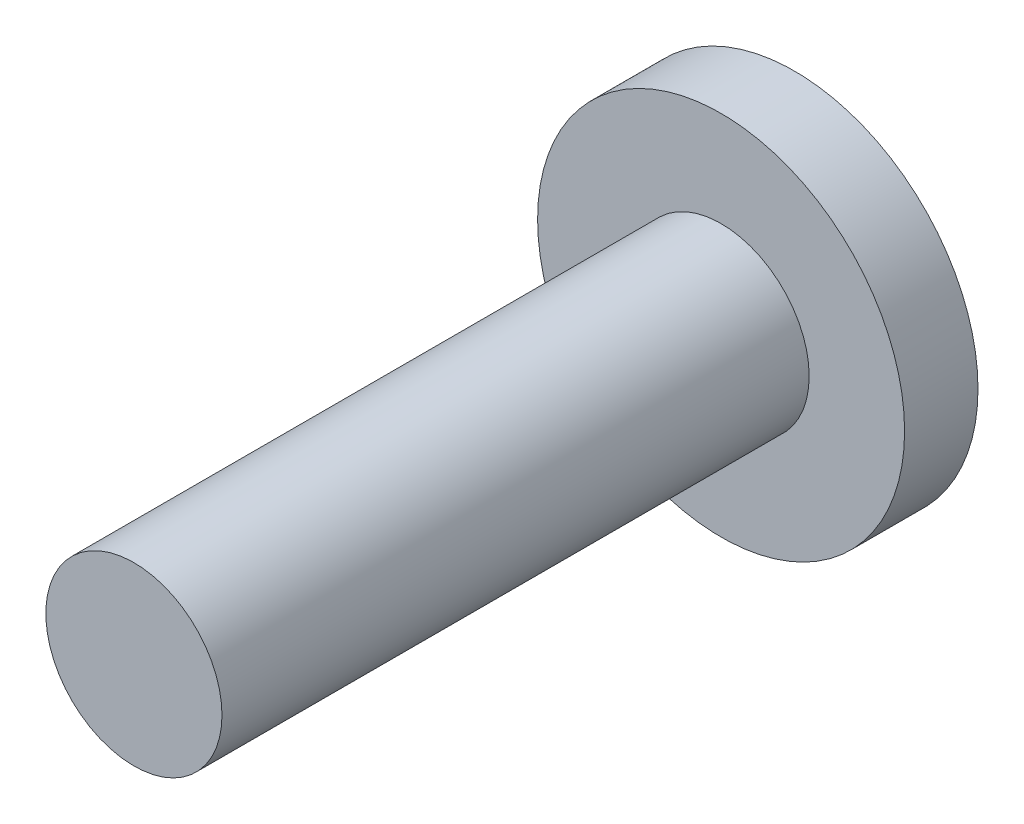
SolidWorks part; units mm, degrees
material "AISI 304"
ref_plane "前视基准面" through (0, 0, 0) normal (0, 0, 1) x (1, 0, 0)
ref_plane "上视基准面" through (0, 0, 0) normal (0, 1, 0) x (1, 0, 0)
ref_plane "右视基准面" through (0, 0, 0) normal (1, 0, 0) x (0, 0, -1)
other "Configuration Table"
sketch "草图1" plane through (0, 0, 0) normal (0, 0, 1) x (1, 0, 0)
  circle A0 centre (0, 0) radius 6.25
  dimension "D1" = 12.5
extrude "凸台-拉伸1" add sketch "草图1" along normal blind 2.5
sketch "草图2" plane through (0, 0, 2.5) normal (0, 0, 1) x (1, 0, 0)
  circle A0 centre (0, 0) radius 3
  dimension "D1" = 6
extrude "凸台-拉伸2" add sketch "草图2" along normal blind 20
sketch "草图3" plane through (0, 0, 0) normal (0, 0, -1) x (-1, 0, 0)
  line L1 (2.3094, 0) -> (1.1547, 2)
  line L2 (1.1547, 2) -> (-1.1547, 2)
  line L3 (-1.1547, 2) -> (-2.3094, 0)
  line L4 (-2.3094, 0) -> (-1.1547, -2)
  line L5 (-1.1547, -2) -> (1.1547, -2)
  line L6 (1.1547, -2) -> (2.3094, 0)
  circle A0 centre (0, 0) radius 2 construction
extrude "切除-拉伸1" cut sketch "草图3" against normal blind 1
